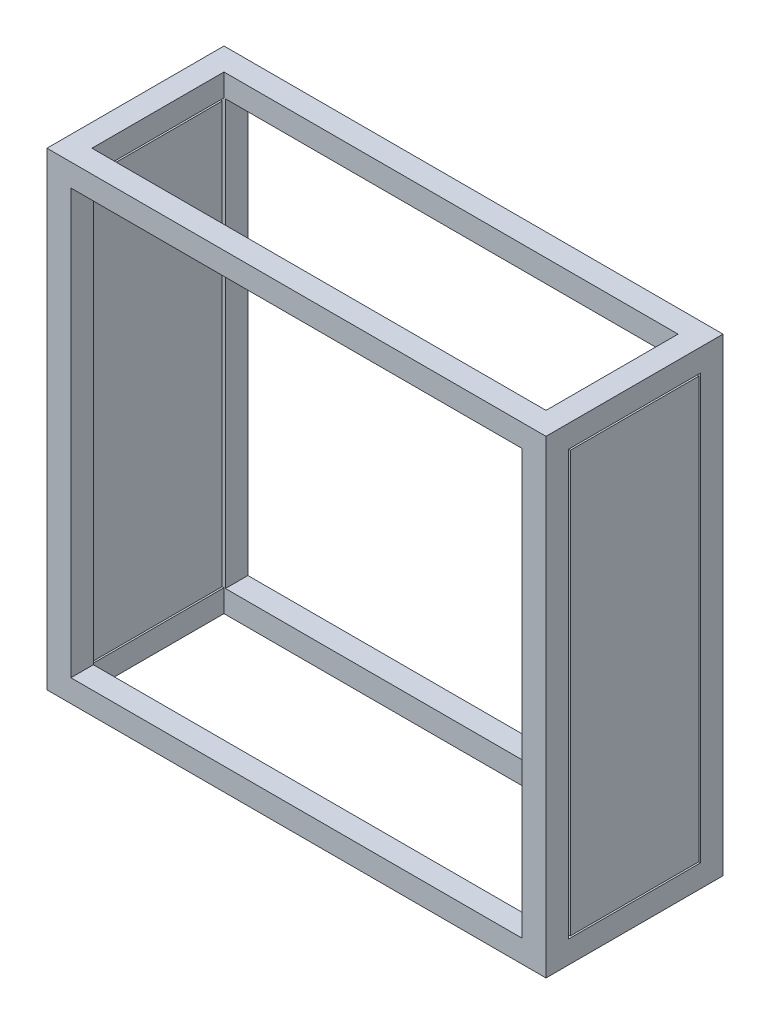
SolidWorks part; units mm, degrees
ref_plane "Alzado" through (0, 0, 0) normal (0, 0, 1) x (1, 0, 0)
ref_plane "Planta" through (0, 0, 0) normal (0, 1, 0) x (1, 0, 0)
ref_plane "Vista lateral" through (0, 0, 0) normal (1, 0, 0) x (0, 0, -1)
sketch "Croquis1" plane through (0, 0, 0) normal (0, 0, 1) x (1, 0, 0)
  line L1 (-281.9, 265) -> (281.9, 265)
  line L2 (-281.9, 265) -> (-281.9, -265)
  line L3 (-281.9, -265) -> (281.9, -265)
  line L4 (281.9, 265) -> (281.9, -265)
  line L5 (-281.9, 265) -> (281.9, -265) construction
  line L6 (-281.9, -265) -> (281.9, 265) construction
  line L7 (-254.8802, 239.6) -> (254.8802, 239.6)
  line L8 (-254.8802, 239.6) -> (-254.8802, -239.6)
  line L9 (-254.8802, -239.6) -> (254.8802, -239.6)
  line L10 (254.8802, 239.6) -> (254.8802, -239.6)
  line L11 (-254.8802, 239.6) -> (254.8802, -239.6) construction
  line L12 (-254.8802, -239.6) -> (254.8802, 239.6) construction
  point P0 (0, 0)
  point P6 (0, 0)
  dimension "D1" = 563.8
  dimension "D2" = 530
  dimension "D3" = 25.4
extrude "Saliente-Extruir1" add sketch "Croquis1" against normal blind 200
sketch "Croquis2" plane through (281.9, 0, 0) normal (1, 0, 0) x (0, 0, -1)
  line L0 (0, 0) -> (200, 0) construction
  line L1 (200, -265) -> (200, 265) construction
  line L2 (200, 0) -> (100, 0) construction
  line L3 (100, 0) -> (100, 265) construction
  line L4 (200, 265) -> (0, 265) construction
  line L5 (0, -265) -> (0, 265) construction
  line L6 (25.4, 239.6) -> (174.6, 239.6)
  line L7 (25.4, 239.6) -> (25.4, -239.6)
  line L8 (25.4, -239.6) -> (174.6, -239.6)
  line L9 (174.6, 239.6) -> (174.6, -239.6)
  line L10 (25.4, 239.6) -> (174.6, -239.6) construction
  line L11 (25.4, -239.6) -> (174.6, 239.6) construction
  dimension "D1" = 25.4
  dimension "D2" = 25.4
extrude "Cortar-Extruir1" cut sketch "Croquis2" against normal up to surface (563.8 mm away) up to face at (-281.9, 0, -100)
sketch "Croquis3" plane through (0, 265, 0) normal (0, 1, 0) x (1, 0, 0)
  line L0 (0, 0) -> (0, 200) construction
  line L1 (281.9, 200) -> (-281.9, 200) construction
  line L2 (0, 200) -> (0, 100) construction
  line L3 (0, 100) -> (-281.9, 100) construction
  line L4 (-281.9, 200) -> (-281.9, 0) construction
  line L5 (281.9, 200) -> (281.9, 0) construction
  line L6 (256.5, 174.6) -> (-256.5, 174.6)
  line L7 (256.5, 174.6) -> (256.5, 25.4)
  line L8 (256.5, 25.4) -> (-256.5, 25.4)
  line L9 (-256.5, 174.6) -> (-256.5, 25.4)
  line L10 (256.5, 174.6) -> (-256.5, 25.4) construction
  line L11 (256.5, 25.4) -> (-256.5, 174.6) construction
  line L12 (281.9, 0) -> (-281.9, 0) construction
  dimension "D1" = 25.4
  dimension "D2" = 25.4
extrude "Cortar-Extruir2" cut sketch "Croquis3" against normal blind 410
sketch "Croquis4" plane through (0, -265, 0) normal (0, -1, 0) x (1, 0, 0)
  line L0 (0, 0) -> (0, -200) construction
  line L1 (-281.9, -200) -> (281.9, -200) construction
  line L2 (0, -200) -> (0, -100) construction
  line L3 (0, -100) -> (255.26, -100) construction
  line L4 (-281.9, 0) -> (281.9, 0) construction
  line L5 (256.5, -25.4) -> (-256.5, -25.4)
  line L6 (256.5, -25.4) -> (256.5, -174.6)
  line L7 (256.5, -174.6) -> (-256.5, -174.6)
  line L8 (-256.5, -25.4) -> (-256.5, -174.6)
  line L9 (256.5, -25.4) -> (-256.5, -174.6) construction
  line L10 (256.5, -174.6) -> (-256.5, -25.4) construction
  line L11 (281.9, -200) -> (281.9, 0) construction
  dimension "D1" = 25.4
  dimension "D2" = 25.4
extrude "Cortar-Extruir3" cut sketch "Croquis4" against normal blind 40
sketch "Croquis5" plane through (281.9, 0, 0) normal (1, 0, 0) x (0, 0, -1)
  line L0 (174.6, -239.6) -> (174.6, 239.6) construction
  line L1 (27.4, 237.6) -> (172.6, 237.6)
  line L2 (27.4, 237.6) -> (27.4, -237.6)
  line L3 (27.4, -237.6) -> (172.6, -237.6)
  line L4 (172.6, 237.6) -> (172.6, -237.6)
  line L5 (27.4, 237.6) -> (172.6, -237.6) construction
  line L6 (27.4, -237.6) -> (172.6, 237.6) construction
  line L7 (174.6, 239.6) -> (25.4, 239.6) construction
  line L8 (25.4, -239.6) -> (174.6, -239.6) construction
  line L9 (25.4, 239.6) -> (25.4, -239.6) construction
  point P0 (100, 0)
  dimension "D1" = 2
  dimension "D2" = 2
  dimension "D3" = 2
  dimension "D4" = 2
extrude "Saliente-Extruir2" add sketch "Croquis5" against normal blind 25.4 separate body
sketch "Croquis6" plane through (-281.9, 0, 0) normal (-1, 0, 0) x (0, 0, 1)
  line L0 (-172.6, 237.6) -> (-27.4, 237.6)
  line L1 (-27.4, 237.6) -> (-27.4, -237.6)
  line L2 (-27.4, -237.6) -> (-172.6, -237.6)
  line L3 (-172.6, -237.6) -> (-172.6, 237.6)
extrude "Saliente-Extruir3" add sketch "Croquis6" against normal blind 25.4 separate body
sketch "Croquis7" plane through (-281.9, 0, 0) normal (-1, 0, 0) x (0, 0, 1)
  line L0 (-200, 265) -> (-208.31, 265)
  line L1 (-200, 265) -> (0, 265) construction
  line L2 (-208.31, 265) -> (-208.31, -164.6)
  line L3 (-208.31, -164.6) -> (0, -164.6) construction
  line L4 (0, 265) -> (0, -265) construction
  line L5 (-208.31, 265) -> (0, 265) construction
  line L6 (0, 265) -> (0, -164.6) construction
  line L7 (-208.31, 239.6) -> (-25.4, 239.6) construction
  line L8 (-174.6, 239.6) -> (-25.4, 239.6) construction
  line L9 (-25.4, 239.6) -> (-25.4, -164.6) construction
  line L10 (-25.4, -239.6) -> (-174.6, -239.6) construction
  line L11 (-208.31, -164.6) -> (-200, -164.6)
  line L12 (-200, 265) -> (-200, -265) construction
  line L13 (-200, -164.6) -> (-200, 265)
  dimension "D2" = 75
sketch "Croquis8" plane through (-281.9, 0, 0) normal (-1, 0, 0) x (0, 0, 1)
  line L0 (-208.31, 237.6) -> (-208.31, -159)
  line L1 (-27.4, 237.6) -> (-172.6, 237.6) construction
  line L2 (-27.4, -159) -> (-208.31, -159)
  line L3 (-27.4, -237.6) -> (-27.4, 237.6) construction
  line L4 (-208.31, 237.6) -> (-27.4, 237.6)
  line L5 (-27.4, 237.6) -> (-27.4, -159)
sketch "Croquis9" plane through (-281.9, 0, 0) normal (-1, 0, 0) x (0, 0, 1)
  line L0 (-27.4, 0) -> (-172.6, 0) construction
  line L1 (-27.4, -237.6) -> (-27.4, 237.6) construction
  line L2 (-172.6, 237.6) -> (-172.6, -237.6) construction
  line L3 (-172.6, 0) -> (-100, 0) construction
  line L4 (-100, 0) -> (-100, 237.6) construction
  line L5 (-27.4, 237.6) -> (-172.6, 237.6) construction
  line L7 (-27.4, -237.6) -> (-172.6, -237.6)
  line L8 (-27.4, -237.6) -> (-27.4, 237.6)
  line L9 (-27.4, 237.6) -> (-172.6, 237.6)
  line L10 (-172.6, -237.6) -> (-172.6, 237.6)
  line L11 (-27.4, -237.6) -> (-172.6, 237.6) construction
  line L12 (-27.4, 237.6) -> (-172.6, -237.6) construction
extrude "Cortar-Extruir4" cut sketch "Croquis9" against normal blind 10
sketch "Croquis10" plane through (0, -265, 0) normal (0, -1, 0) x (1, 0, 0)
  line L0 (281.9, -200) -> (281.9, -162) construction
  line L1 (281.9, -200) -> (281.9, 0) construction
  line L2 (281.9, -162) -> (256.5, -162) construction
  line L3 (256.5, -174.6) -> (256.5, -25.4) construction
  line L4 (256.5, -162) -> (269.2, -162) construction
  line L5 (0, 0) -> (0, -200) construction
  line L6 (-281.9, -200) -> (281.9, -200) construction
  line L7 (0, -200) -> (0, -100) construction
  line L8 (0, -100) -> (-97.3006, -100) construction
  line L9 (256.5, -38) -> (269.2, -38) construction
  circle A0 centre (269.2, -162) radius 3.175
  circle A1 centre (-269.2, -162) radius 3.175
  circle A2 centre (-269.2, -38) radius 3.175
  circle A3 centre (269.2, -38) radius 3.175
  dimension "D2" = 6.35
  dimension "D1" = 38
extrude "Cortar-Extruir5" cut sketch "Croquis10" against normal blind 10
